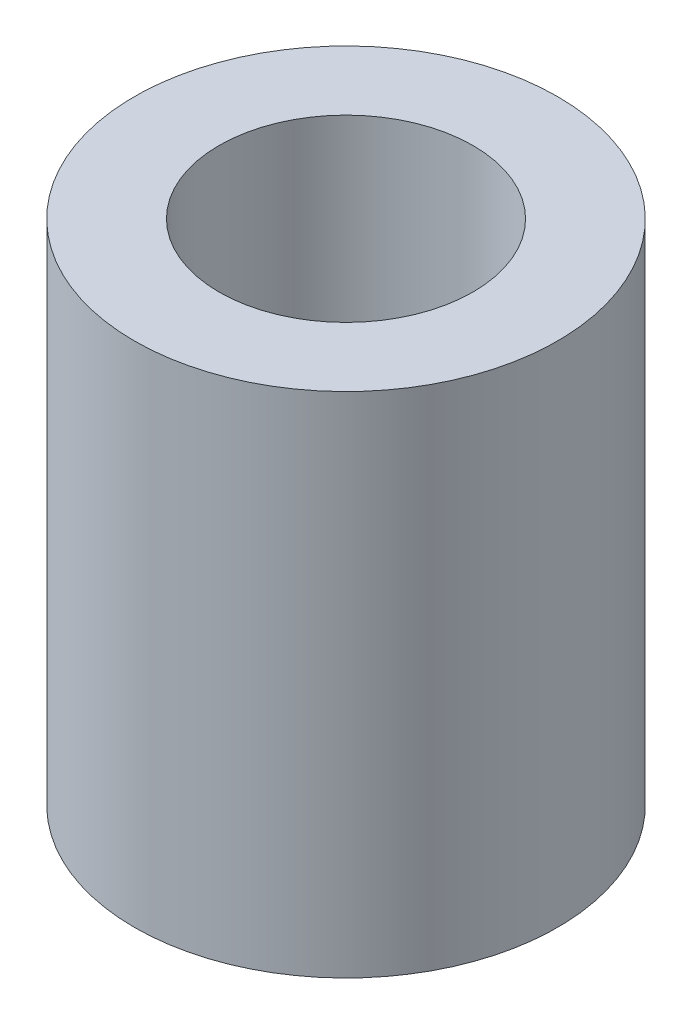
SolidWorks part; units mm, degrees
ref_plane "Front Plane" through (0, 0, 0) normal (0, 0, 1) x (1, 0, 0)
ref_plane "Top Plane" through (0, 0, 0) normal (0, 1, 0) x (1, 0, 0)
ref_plane "Right Plane" through (0, 0, 0) normal (1, 0, 0) x (0, 0, -1)
sketch "Sketch1" plane through (0, 0, 0) normal (0, 1, 0) x (1, 0, 0)
  circle A0 centre (0, 0) radius 5
  circle A1 centre (0, 0) radius 3
  dimension "D1" = 10
  dimension "D2" = 6
extrude "Boss-Extrude1" add sketch "Sketch1" along normal blind 12
equation "\"column angle\" = 45deg "
equation "\"short_bearing_outer_width\" = 10mm "
equation "\"wheel base\" = 1561mm "
equation "\"track\" = 1354mm "
equation "\"turning radius\" = 2000mm "
equation "\"turn to lock\" = 0.75mm "
equation "\"steering arm length\" = 100mm "
equation "\"primary shaft small diameter\" = 16mm "
equation "\"primary shaft large diameter\" = 24mm "
equation "\"secondary shaft small diameter\" = 16mm "
equation "\"secondary shaft large diameter\" = 25mm "
equation "\"steering column length\" = 555mm "
equation "\"keyway_height\" = 1.39mm "
equation "\"keyway_width\" = 2.78mm "
equation "\"keyway_length\" = 30mm "
equation "\"steering wheel bolt width\" = 6mm "
equation "\"steering wheel bolt length\" = 40mm "
equation "\"bushing length\" = 40mm "
equation "\"bushing thickness\" = 3mm "
equation "\"u_joint clearance\" = 30mm "
equation "\"u_joint thickness\" = 7.5mm "
equation "\"horizontal shaft length\" = 90mm "
equation "\"column bushing diameter\" = \"primary shaft small diameter\" + 4 "
equation "\"column bushing distance\" = \"steering column length\"/4 "
equation "\"pinion width\" = 26.5mm "
equation "\"pin hole diameter\" = 10mm "
equation "\"rack hole to hole\" = 500mm "
equation "\"rack length\" = \"rack hole to hole\" + \"pin hole diameter\"*2 "
equation "\"max turning angle\" = atn(\"wheel base\" / (\"turning radius\" - 0.5 * \"track\")) "
equation "\"max travel\" = 2 * \"steering arm length\" * sin(0.5 * \"max turning angle\") "
equation "\"pitch diameter\" = \"max travel\"/(pi * \"turn to lock\") "
equation "\"number of teeth\" = 18mm "
equation "\"pressure angle\" = 20deg "
equation "\"module\" = \"pitch diameter\" / \"number of teeth\" "
equation "\"tie rod length\" = 305mm "
equation "\"tie rod inner diameter\" = 6.6mm "
equation "\"tie rod outer diameter\" = 8.1mm "
equation "\"D2@Sketch1\"=6"
